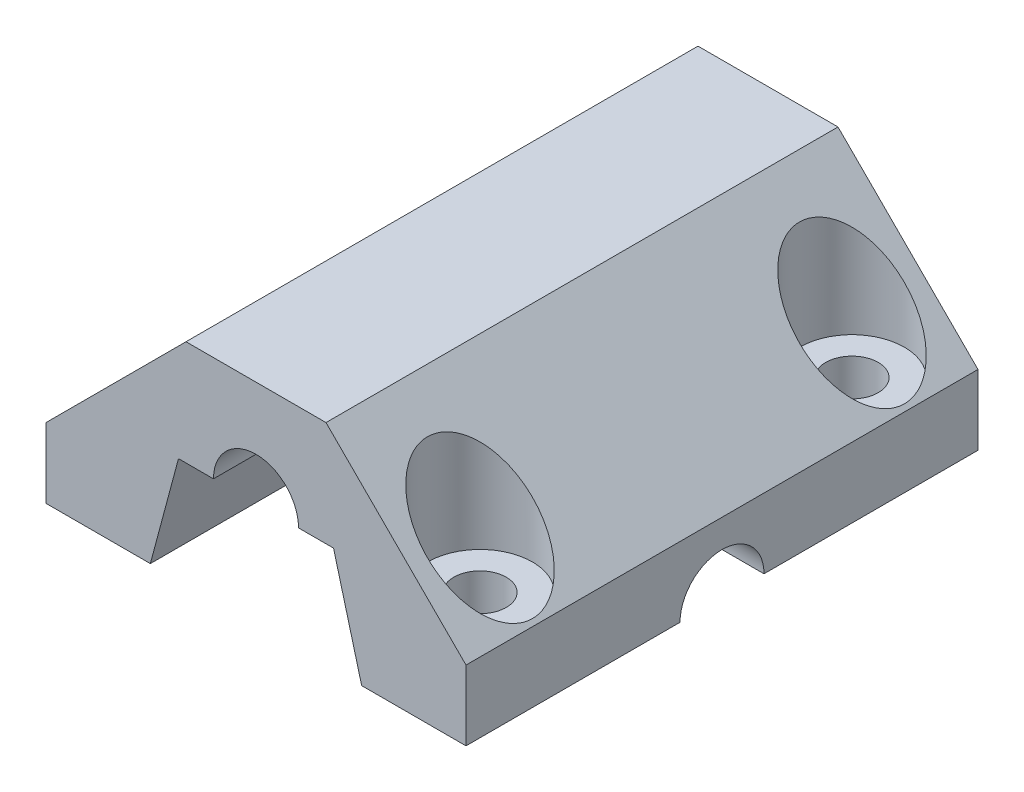
SolidWorks part; units mm, degrees
ref_plane "Ön Düzlem" through (0, 0, 0) normal (0, 0, 1) x (1, 0, 0)
ref_plane "Üst Düzlem" through (0, 0, 0) normal (0, 1, 0) x (1, 0, 0)
ref_plane "Sağ Düzlem" through (0, 0, 0) normal (1, 0, 0) x (0, 0, -1)
sketch "Sketch1" plane through (0, 0, 0) normal (0, 0, 1) x (1, 0, 0)
  line L1 (30, -15) -> (-30, -15)
  line L2 (30, -15) -> (30, 15)
  line L3 (30, 15) -> (-30, 15)
  line L4 (-30, -15) -> (-30, 15)
  line L5 (30, -15) -> (-30, 15) construction
  line L6 (30, 15) -> (-30, -15) construction
  point P0 (0, 0)
  dimension "D1" = 60
  dimension "30" = 30
extrude "Boss-Extrude1" add sketch "Sketch1" along normal mid plane 73.14
sketch "Sketch2" plane through (30, 0, 0) normal (1, 0, 0) x (0, 0, -1)
  line L0 (-36.57, -15) -> (36.57, -15) construction
  line L1 (-6, -15) -> (6, -15)
  line L2 (6, -15) -> (5.8249, -15.1366)
  arc A0 (-6, -15) -> (6, -15) centre (0, -15) cw
  line M4 (-36.57, -15) -> (36.57, -15)
  dimension "D1" = 6
extrude "Cut-Extrude1" cut sketch "Sketch2" against normal up to surface (60 mm away) contours A0 M4 up to face at (-30, 0, 0)
sketch "Sketch3" plane through (0, 0, 36.57) normal (0, 0, 1) x (1, 0, 0)
  line L0 (6.075, 0) -> (11.075, 0)
  line L1 (-30, -15) -> (30, -15) construction
  line L2 (-6.075, 0) -> (-11.075, 0)
  line L3 (-15.0942, -15) -> (15.0942, -15)
  line L4 (0, 13.385) -> (0, -19.9591) construction
  line L5 (30, -15) -> (30, 15) construction
  line L6 (11.075, 0) -> (15.0942, -15)
  line L7 (-11.075, 0) -> (-15.0942, -15)
  arc A0 (6.075, 0) -> (-6.075, 0) centre (0, 0) ccw
  dimension "D4" = 15
  dimension "12" = 12.15
  dimension "D1" = 5
  dimension "D3" = 75
  dimension "D5" = 30
  dimension "D6" = 5
  dimension "D7" = 75
extrude "Cut-Extrude2" cut sketch "Sketch3" against normal up to surface (73.14 mm away) up to face at (0, 0, -36.57)
sketch "Sketch4" plane through (0, 0, 36.57) normal (0, 0, 1) x (1, 0, 0)
  line L0 (30, 15) -> (30, -5)
  line L2 (30, -15) -> (30, 15) construction
  line L3 (30, -5) -> (10, 15)
  line L4 (30, 15) -> (-30, 15) construction
  line L5 (10, 15) -> (30, 15)
  line L6 (0, 20.3589) -> (0, -23.7913) construction
  line L7 (-30, 15) -> (-30, -5)
  line L8 (-10, 15) -> (-30, 15)
  line L9 (-30, -5) -> (-10, 15)
  dimension "D1" = 20
  dimension "20" = 20
extrude "Cut-Extrude3" cut sketch "Sketch4" against normal up to surface (73.14 mm away) up to face at (0, -2.3925, -36.57)
ref_plane "Plane1" through (0, 15, 0) normal (0, 1, 0) x (1, 0, 0)
sketch "Sketch5" plane through (0, 15, 0) normal (0, 1, 0) x (1, 0, 0)
  line L0 (0, -43.2701) -> (0, 38.8321) construction
  line L1 (-54.9807, 0) -> (44.2894, 0) construction
  line L2 (10, -36.57) -> (30, -36.57) construction
  line L3 (30, 36.57) -> (30, -36.57) construction
  circle A0 centre (22, -26.57) radius 3.75
  circle A1 centre (-22, -26.57) radius 3.75
  circle A2 centre (22, 26.57) radius 3.75
  circle A3 centre (-22, 26.57) radius 3.75
  dimension "D3" = 7.5
  dimension "D1" = 10
  dimension "D2" = 8
extrude "Cut-Extrude4" cut sketch "Sketch5" against normal up to surface (30 mm away) up to face at (22.5471, -15, 21.285)
sketch "Sketch6" plane through (0, 15, 0) normal (0, 1, 0) x (1, 0, 0)
  line L0 (0, 39.416) -> (0, -38.5985) construction
  line L1 (-43.185, 0) -> (47.2091, 0) construction
  circle A0 centre (22, -26.57) radius 7.5
  circle A1 centre (-22, -26.57) radius 7.5
  circle A2 centre (22, 26.57) radius 7.5
  circle A3 centre (-22, 26.57) radius 7.5
  dimension "1" = 15
extrude "Cut-Extrude5" cut sketch "Sketch6" against normal blind 20
